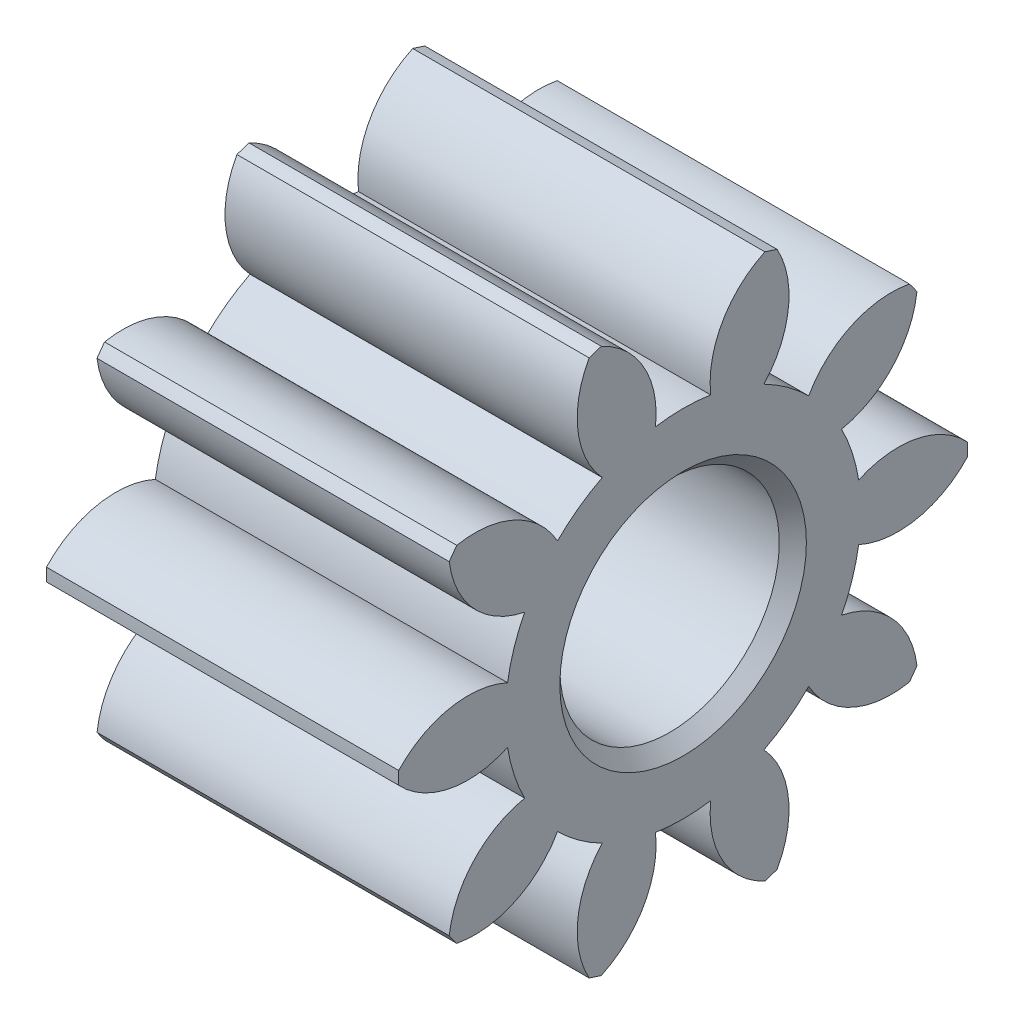
SolidWorks part; units mm, degrees
ref_plane "Plane1" through (0, 0, 0) normal (0, 0, 1) x (1, 0, 0)
ref_plane "Plane2" through (0, 0, 0) normal (0, 1, 0) x (1, 0, 0)
ref_plane "Plane3" through (0, 0, 0) normal (1, 0, 0) x (0, 0, -1)
sketch "HoldingSke" plane through (0, 0, 0) normal (0, 1, 0) x (1, 0, 0)
  line L0 (0, 0) -> (0.5627, -0.0992)
  line L1 (-15, 0) -> (100, 0) construction
  line L2 (0, 0) -> (-2.1039, 2.3779)
  line L3 (0, 0) -> (-11.863, 4.5341)
  line L4 (0, 0) -> (8.5048, 1.4996)
  line L5 (0, 0) -> (-46.8476, -17.4728)
  line L6 (0, 0) -> (-10.7765, -7.2709)
  line L7 (-2.1039, 2.3779) -> (8.6586, 51.2059)
  line L8 (-76.2, 54.61) -> (-75.7, 54.61)
  line L9 (-71.009, 38.7566) -> (-53.1078, 45.2721)
  line L10 (-76.2, 71.12) -> (104.1128, 71.12)
  line L11 (0, 0) -> (-13, 0)
  line L12 (-76.2, 101.6) -> (-76.147, 101.6)
  line L13 (24.9733, 27.94) -> (52.9518, 28.4284)
  line L14 (24.9733, 27.94) -> (24.9743, 27.94)
  line L15 (24.9733, 27.94) -> (100.4006, 29.5858)
  line L16 (-63.627, -1.75) -> (-12.827, -1.75)
  circle A0 centre (0, 0) radius 1.5
  circle A1 centre (0, 0) radius 6.5615
  circle A2 centre (0, 0) radius 37.5
  circle A3 centre (0, 0) radius 1.5
  dimension "MHD" = 13.123
  dimension "Hub_dia" = 75
  dimension "Bore" = 3
  dimension "MBD" = 3
  dimension "Num_teeth" = 10
  dimension "Pitch" = 0.5714
  dimension "Overall_len" = 50
  dimension "Show_teeth" = 10
  dimension "Thickness" = 13
  dimension "OAL" = 50.0001
  dimension "T_dim" = 0.5
  dimension "Ap" = 20
  dimension "H" = 19.05
  dimension "Pitch_radius" = 180.3128
  dimension "Width" = 13
  dimension "Backlash" = 0.053
  dimension "Addendum_fac" = 1
  dimension "Dedendum_fac" = 1.25
  dimension "Clearance_fac" = 0.25
  dimension "Dedendum_add" = 0.001
  dimension "Module" = 1.75
sketch "BasProSke" plane through (0, 0, 0) normal (0, 1, 0) x (1, 0, 0)
  line L0 (-10, 0) -> (60, 0) construction
  line L1 (0, 0) -> (0, 10.5)
  line L2 (0, 0) -> (13, 0)
  line L3 (13, 0) -> (13, 10.5)
  line L4 (13, 10.5) -> (0, 10.5)
  dimension "Thickness" = 13
  dimension "Diameter" = 21
revolve "Base-Revolve" add sketch "BasProSke" angle 360 about L0
sketch "TooCutSke" plane through (0, 0, 0) normal (1, 0, 0) x (0, 0, -1)
  line L1 (0, 0) -> (0, 107) construction
  line L2 (0, 0) -> (-1.4614, 8.6271) construction
  line L3 (0, 0) -> (-5.35, 16.4656) construction
  line L4 (-1.4614, 8.6271) -> (-2.675, 8.2328) construction
  arc A0 (1.0196, 6.4818) -> (-1.0196, 6.4818) centre (0, 0) ccw
  arc A1 (3.0536, 10.0727) -> (-3.0536, 10.0727) centre (0, 0) ccw
  circle A2 centre (0, 0) radius 8.75 construction
  circle A3 centre (0, 0) radius 8.2223 construction
  arc A4 (-1.0196, 6.4818) -> (-3.0536, 10.0727) centre (-4.4964, 6.8839) ccw
  arc A5 (3.0536, 10.0727) -> (1.0196, 6.4818) centre (4.4964, 6.8839) ccw
  dimension "Root_dia" = 13.123
  dimension "Overcut_dia" = 21.0508
  dimension "Pitch_dia" = 17.5
  dimension "Base_dia" = 16.4446
  dimension "Flank_rad" = 3.5
  dimension "Half_ang" = 18
  dimension "Half_CT" = 1.2761
extrude "ToothCut" cut sketch "TooCutSke" along normal through all
fillet "Breaks" [suppressed] radius 0.035
fillet "RootFillets" [suppressed] radius 0.4385
pattern_circular "TeethCuts" count 10 every 36 about axis through (-10, 0, 0) along (1, 0, 0) of "ToothCut", "RootFillets", "Breaks"
sketch "HubNeaOneSke" plane through (0, 0, 0) normal (-1, 0, 0) x (0, 0, 1)
  circle A0 centre (0, 0) radius 6.5615
  dimension "Diameter" = 13.123
extrude "HubNearOne" [suppressed] add sketch "HubNeaOneSke" along normal blind 37.0001
sketch "HubNeaBotSke" plane through (0, 0, 0) normal (-1, 0, 0) x (0, 0, 1)
  circle A0 centre (0, 0) radius 6.5615
  dimension "Diameter" = 13.123
extrude "HubNearBoth" [suppressed] add sketch "HubNeaBotSke" along normal blind 18.5
ref_plane "FarPln" through (13, 0, 0) normal (1, 0, 0) x (0, 0, -1)
sketch "HubFarSke" plane through (13, 0, 0) normal (1, 0, 0) x (0, 0, -1)
  circle A0 centre (0, 0) radius 6.5615
  dimension "Diameter" = 13.123
extrude "HubFar" [suppressed] add sketch "HubFarSke" along normal blind 18.5
sketch "BorSke" plane through (0, 0, 0) normal (1, 0, 0) x (0, 0, -1)
  circle A0 centre (0, 0) radius 1.5
  dimension "Diameter" = 3
extrude "Bore" cut sketch "BorSke" along normal mid plane 100.0001
sketch "KeySke" plane through (0, 0, 0) normal (1, 0, 0) x (0, 0, -1)
  line L0 (-0.6, 0) -> (-0.6, 2)
  line L1 (-0.6, 2) -> (0.6, 2)
  line L2 (0.6, 2) -> (0.6, 0)
  line L3 (0, 0) -> (0, 34) construction
  line L4 (-0.6, 0) -> (0.6, 0)
  dimension "Offset" = 2
  dimension "Width" = 1.2
extrude "Keyway" [suppressed] cut sketch "KeySke" along normal mid plane 100.0001
pattern_circular "Keyway2" [suppressed] count 2 every 90 about axis through (-10, 0, 0) along (1, 0, 0)
sketch "Sketch1" plane through (0, 0, 0) normal (-1, 0, 0) x (0, 0, 1)
  circle A0 centre (0, 0) radius 4.05
  dimension "D1" = 8.1
extrude "Cut-Extrude1" cut sketch "Sketch1" against normal up to next
chamfer "Chamfer1" distance 0.5 angle 45 2 edges at (0, 0, 4.05) (13, 0, 4.05)
equation "' \"Module@HoldingSke\" = 6.35"
equation "' \"Num_teeth@HoldingSke\" = 12"
equation "' \"Ap@HoldingSke\" =  20"
equation "' \"Ap@HoldingSke\" = 20"
equation "' \"Width@HoldingSke\" = 0.5 * 25.4"
equation "' \"Hub_dia@HoldingSke\"= 1 * 25.4"
equation "' \"Hub_dia@HoldingSke\" = 1 * 25.4"
equation "' \"Overall_len@HoldingSke\" = 1.0 * 25.4"
equation "' \"Bore@HoldingSke\" = 0.75 * 25.4"
equation "' \"T_dim@HoldingSke\" = 0.1 * 25.4"
equation "' \"Width@KeySke\" = 0.25 * 25.4"
equation "' \"Show_teeth@HoldingSke\" = 13"
equation "' \"Backlash@HoldingSke\" = 0.009 * 25.4"
equation "' \"Addendum_fac@HoldingSke\" = 1.0"
equation "' \"Dedendum_fac@HoldingSke\" = 1.25"
equation "' \"Dedendum_add@HoldingSke\" = 0.00005 * 25.4"
equation "' \"Clearance_fac@HoldingSke\" = 0.25"
equation "\"Pitch@HoldingSke\" = 1 / \"Module@HoldingSke\""
equation "\"Overcut_dia@TooCutSke\" = (\"Num_teeth@HoldingSke\" + 2 * \"Addendum_fac@HoldingSke\") / \"Pitch@HoldingSke\" + 0.002 * 25.4"
equation "\"Pitch_dia@TooCutSke\" = \"Num_teeth@HoldingSke\" / \"Pitch@HoldingSke\""
equation "\"Base_dia@TooCutSke\" = \"Num_teeth@HoldingSke\" / \"Pitch@HoldingSke\" * cos((\"Ap@HoldingSke\"  * 3.14159265 / 180))"
equation "\"Root_dia@TooCutSke\" = (\"Num_teeth@HoldingSke\" + 2) / \"Pitch@HoldingSke\" - 2 * (\"Addendum_fac@HoldingSke\" + \"Dedendum_fac@HoldingSke\") / \"Pitch@HoldingSke\" - \"Dedendum_add@HoldingSke\" * 2"
equation "\"Half_ang@TooCutSke\" = 180 / \"Num_teeth@HoldingSke\""
equation "\"Half_CT@TooCutSke\" = \"Num_teeth@HoldingSke\" / \"Pitch@HoldingSke\" * sin((3.14159265 / 2 / \"Num_teeth@HoldingSke\")) / 2 - 7 * \"Backlash@HoldingSke\" / 4"
equation "\"Flank_rad@TooCutSke\" = \"Num_teeth@HoldingSke\" / \"Pitch@HoldingSke\" / 5"
equation "\"Radius@RootFillets\" = \"Clearance_fac@HoldingSke\" / \"Pitch@HoldingSke\" + \"Dedendum_add@HoldingSke\""
equation "\"Break_rad@Breaks\" = 0.02 / \"Pitch@HoldingSke\""
equation "\"Thickness@HoldingSke\" = \"Width@HoldingSke\""
equation "\"OAL@HoldingSke\" = \"Thickness@HoldingSke\""
equation "\"MHD@HoldingSke\" = (\"Num_teeth@HoldingSke\" + 2) / \"Pitch@HoldingSke\" - 2 * (\"Addendum_fac@HoldingSke\" + \"Dedendum_fac@HoldingSke\")  / \"Pitch@HoldingSke\" - \"Dedendum_add@HoldingSke\" * 2"
equation "\"MBD@HoldingSke\" = (\"Num_teeth@HoldingSke\" + 2) / \"Pitch@HoldingSke\" - 2 * (\"Addendum_fac@HoldingSke\" + \"Dedendum_fac@HoldingSke\")  / \"Pitch@HoldingSke\" - \"Dedendum_add@HoldingSke\" * 2 - 0.002 * 25.4"
equation "\"MHD@HoldingSke\" = ((sgn( \"MHD@HoldingSke\" - \"Hub_dia@HoldingSke\" )-1)*( \"MHD@HoldingSke\" - \"Hub_dia@HoldingSke\" ))/-2+ \"Hub_dia@HoldingSke\""
equation "\"MBD@HoldingSke\" = ((sgn( \"MBD@HoldingSke\" - \"Bore@HoldingSke\" )-1)*( \"MBD@HoldingSke\" - \"Bore@HoldingSke\" ))/-2+ \"Bore@HoldingSke\""
equation "\"OAL@HoldingSke\" = ((sgn( \"OAL@HoldingSke\" - \"Overall_len@HoldingSke\" )+1)*( \"OAL@HoldingSke\" - \"Overall_len@HoldingSke\" ))/2 + \"Overall_len@HoldingSke\" + 0.000002 * 25.4"
equation "\"Num_teeth@TeethCuts\" = int( \"Show_teeth@HoldingSke\" ) + 1"
equation "\"Num_teeth@TeethCuts\" = ((sgn( \"Num_teeth@TeethCuts\" - \"Num_teeth@HoldingSke\" )-1)*( \"Num_teeth@TeethCuts\" - \"Num_teeth@HoldingSke\" ))/-2+ \"Num_teeth@HoldingSke\""
equation "\"Num_teeth@TeethCuts\" = ((sgn( \"Num_teeth@TeethCuts\" - 2.0)+1)*( \"Num_teeth@TeethCuts\" - 2.0))/2 +2.0"
equation "\"Angle@TeethCuts\" = 360.0 / \"Num_teeth@HoldingSke\""
equation "\"Diameter@BasProSke\" = (\"Num_teeth@HoldingSke\" + 2 * \"Addendum_fac@HoldingSke\") / \"Pitch@HoldingSke\""
equation "\"Thickness@BasProSke\"  = \"Thickness@HoldingSke\""
equation "' \"Fillet_rad@BasProSke\" =  \"Thickness@HoldingSke\" * 0.05"
equation "' \"Fillet_rad@BasProSke\" = \"Thickness@HoldingSke\" * 0.05"
equation "\"MHD@HoldingSke\" = ((sgn( \"MHD@HoldingSke\" - \"Root_dia@TooCutSke\" )-1)*( \"MHD@HoldingSke\" - \"Root_dia@TooCutSke\" ))/-2+ \"Root_dia@TooCutSke\""
equation "\"Diameter@HubNeaOneSke\" = \"MHD@HoldingSke\""
equation "\"Length@HubNearOne\" = \"OAL@HoldingSke\" - \"Thickness@BasProSke\""
equation "\"Diameter@HubNeaBotSke\" = \"MHD@HoldingSke\""
equation "\"Length@HubNearBoth\" = ( \"OAL@HoldingSke\" - \"Thickness@BasProSke\" ) / 2.0"
equation "\"Thickness@FarPln\" = \"Thickness@BasProSke\""
equation "\"Diameter@HubFarSke\" = \"MHD@HoldingSke\""
equation "\"Length@HubFar\" = ( \"OAL@HoldingSke\" - \"Thickness@BasProSke\" ) / 2.0"
equation "\"Diameter@BorSke\" = \"MBD@HoldingSke\""
equation "\"D1@Bore\" = \"OAL@HoldingSke\" * 2.0"
equation "\"D1@Keyway\" = \"OAL@HoldingSke\" * 2.0"
equation "\"Offset@KeySke\" = \"T_dim@HoldingSke\" + \"MBD@HoldingSke\" / 2.0"
